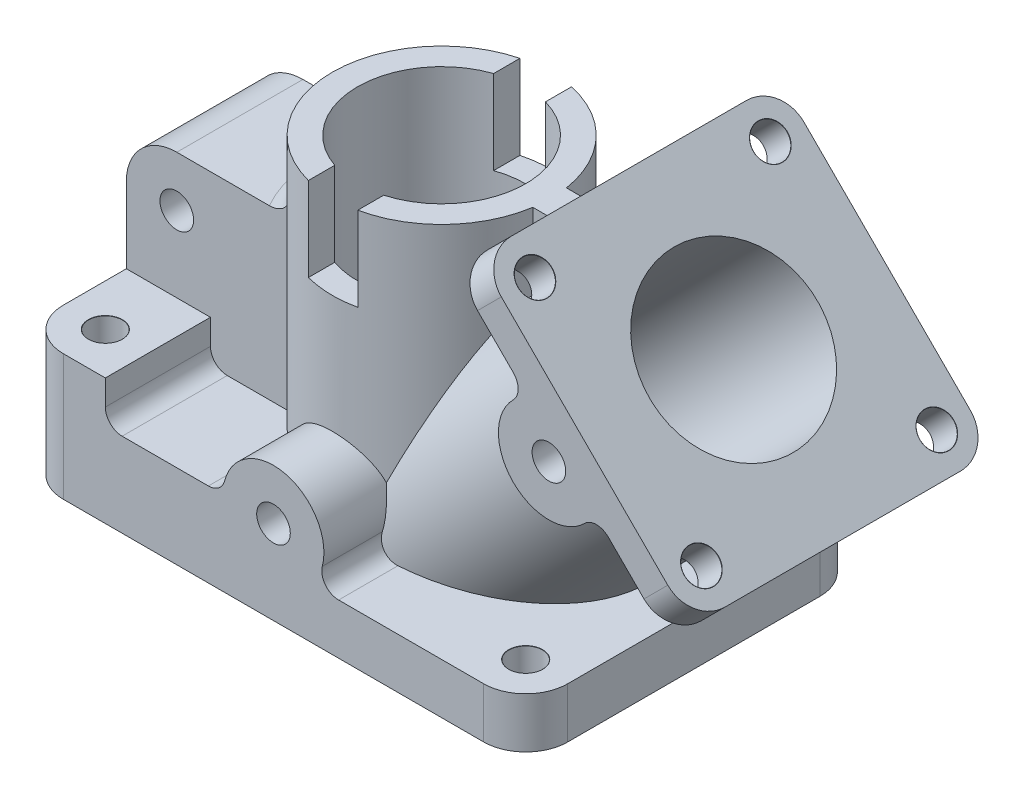
SolidWorks part; units mm, degrees
ref_plane "Front Plane" through (0, 0, 0) normal (0, 0, 1) x (1, 0, 0)
ref_plane "Top Plane" through (0, 0, 0) normal (0, 1, 0) x (1, 0, 0)
ref_plane "Right Plane" through (0, 0, 0) normal (1, 0, 0) x (0, 0, -1)
sketch "Croquis1" plane through (0, 0, 0) normal (0, 0, 1) x (1, 0, 0)
  line L0 (0, 0) -> (0, 15)
  line L1 (0, 15) -> (10, 15)
  line L2 (10, 15) -> (10, 10)
  line L3 (10, 10) -> (24, 10)
  line L4 (34.4721, 6) -> (60, 6)
  line L5 (60, 6) -> (60, 0)
  line L6 (60, 0) -> (0, 0)
  arc A0 (24, 10) -> (34.4721, 6) centre (30, 10) cw
  point P8 (17, 10)
  dimension "D5" = 6
  dimension "D1" = 15
  dimension "D2" = 10
  dimension "D3" = 10
  dimension "D4" = 6
  dimension "D6" = 60
  dimension "D7" = 30
extrude "Saliente-Extruir1" add sketch "Croquis1" along normal mid plane 40
sketch "Croquis2" plane through (0, 0, 20) normal (0, 0, 1) x (1, 0, 0)
  circle A0 centre (30, 10) radius 2
  dimension "D1" = 4
extrude "Cortar-Extruir1" cut sketch "Croquis2" against normal through all
fillet "Redondeo1" radius 2 3 edges at (24, 10, 0) (10, 10, 0) (34.4721, 6, 0)
sketch "Croquis3" plane through (0, 0, 0) normal (0, -1, 0) x (1, 0, 0)
  circle A0 centre (30, 0) radius 13
  dimension "D1" = 26
  dimension "D2" = 30
extrude "Saliente-Extruir2" add sketch "Croquis3" against normal blind 40
sketch "Croquis4" plane through (0, 0, 0) normal (0, 0, 1) x (1, 0, 0)
  line L0 (0, 7.5) -> (0, 30)
  line L1 (0, 15) -> (0, 0) construction
  line L2 (0, 30) -> (19.7656, 30)
  line L3 (19.7656, 30) -> (19.7656, 7.5)
  line L4 (19.7656, 7.5) -> (0, 7.5)
  dimension "D1" = 30
extrude "Saliente-Extruir3" add sketch "Croquis4" along normal mid plane 15
fillet "Redondeo2" radius 2 1 edges at (17, 30, 0)
fillet "Redondeo3" radius 6 1 edges at (0, 30, 0)
sketch "Croquis7" plane through (0, 0, 0) normal (0, 0, 1) x (1, 0, 0)
  line L0 (30, 38.1979) -> (30, 0) construction
  line L1 (0, 0) -> (60, 0) construction
  line L2 (30, 0) -> (65, 35) construction
  point P4 (65, 35)
  point P6 (65, 35)
  point P7 (30, 0)
  dimension "D1" = 45
  dimension "D2" = 35
ref_plane "Plano1" through (65, 35, 0) normal (0.7071, 0.7071, 0) x (0.7071, -0.7071, 0)
sketch "Croquis8" plane through (65, 35, 0) normal (0.7071, 0.7071, 0) x (0.7071, -0.7071, 0)
  line L0 (-27.01, 0) -> (0, 0) construction
  line L1 (18, 18) -> (-18, 18)
  line L2 (18, 18) -> (18, -18)
  line L3 (18, -18) -> (-18, -18)
  line L4 (-18, 18) -> (-18, -18)
  line L5 (18, 18) -> (-18, -18) construction
  line L6 (18, -18) -> (-18, 18) construction
  point P0 (0, 0)
  dimension "D1" = 36
extrude "Saliente-Extruir4" add sketch "Croquis8" against normal blind 4 separate body
sketch "Croquis9" plane through (50, 50, 0) normal (0.7071, 0.7071, 0) x (0, 0, -1)
  line L0 (0, 5.7968) -> (0, -21.2132) construction
  circle A0 centre (0, -21.2132) radius 13
  dimension "D1" = 26
extrude "Saliente-Extruir5" add sketch "Croquis9" against normal blind 41
sketch "Croquis10" plane through (0, 0, 18) normal (0, 0, 1) x (1, 0, 0)
  line L0 (30, 0) -> (65, 35) construction
  line L1 (84.25, 15.75) -> (45.75, 54.25) construction
  circle A0 centre (60.7574, 30.7574) radius 6
  circle A1 centre (60.7574, 30.7574) radius 2
  dimension "D1" = 6
  dimension "D2" = 12
  dimension "D3" = 4
extrude "Saliente-Extruir6" add sketch "Croquis10" against normal blind 36
fillet "Redondeo4" radius 2 4 edges at (66.1716, 28.1716, -14.8523) (58.1716, 36.1716, -14.8523) (66.1716, 28.1716, 14.8523) (58.1716, 36.1716, 14.8523)
fillet "Redondeo5" radius 5 4 edges at (0, 7.5, -20) (60, 3, -20) (0, 7.5, 20) (60, 3, 20)
fillet "Redondeo6" radius 4 4 edges at (76.3137, 20.8579, -18) (50.8579, 46.3137, 18) (50.8579, 46.3137, -18) (76.3137, 20.8579, 18)
hole_wizard "Ø4.0mm Dowel Hole1" positions "Croquis3D1" profile "Croquis12" hole size "Ø4.0" standard "ISO"
sketch3d "Croquis3D1"
  line L0 (52.2721, 42.0711, 14) -> (55.1005, 44.8995, 14) construction
  line L1 (52.2721, 42.0711, -14) -> (55.1005, 44.8995, -14) construction
  line L2 (72.0711, 22.2721, -14) -> (74.8995, 25.1005, -14) construction
  line L3 (72.0711, 22.2721, 14) -> (74.8995, 25.1005, 14) construction
  line L4 (55, 0, 15) -> (55, 6, 15) construction
  line L5 (55, 6, -15) -> (55, 0, -15) construction
  line L6 (5, 0, -15) -> (5, 15, -15) construction
  line L7 (5, 15, 15) -> (5, 0, 15) construction
  point P0 (55.1005, 44.8995, 14)
  point P4 (55.1005, 44.8995, -14)
  point P8 (74.8995, 25.1005, -14)
  point P12 (74.8995, 25.1005, 14)
  point P16 (55, 6, 15)
  point P20 (55, 6, -15)
  point P24 (5, 15, -15)
  point P28 (5, 15, 15)
sketch "Croquis12" plane through (55.1005, 44.8995, 14) normal (0, 0, 1) x (-0.7071, 0.7071, 0)
  line L0 (0, 0) -> (0, 16.2017)
  line L1 (0, 16.2017) -> (2, 15)
  line L2 (2, 15) -> (2, 0.021)
  line L3 (2, 0.021) -> (2.025, 0)
  line L5 (2.025, 0) -> (0, 0)
  line L6 (-2, 0.021) -> (-2.025, 0) construction
  line L10 (0, 16.2017) -> (-2, 15) construction
  line L11 (0, -6.35) -> (0, 107.95) construction
  dimension "Hole Dia." = 4
  dimension "Hole Depth" = 15
  dimension "Near C'Sink Dia." = 4.05
  dimension "Near C'Sink Angle" = 100
  dimension "Drill Angle" = 118
sketch "Croquis15" plane through (0, 0, 0) normal (0, 0, 1) x (1, 0, 0)
  line L0 (34.2168, 40) -> (53.3496, 40)
  line L1 (43, 40) -> (17, 40) construction
  line L2 (53.3496, 40) -> (53.3496, 28.1267)
  line L3 (53.3496, 28.1267) -> (34.2168, 28.1267)
  line L4 (34.2168, 28.1267) -> (34.2168, 40)
extrude "Saliente-Extruir13" add sketch "Croquis15" along normal mid plane 4
sketch "Croquis18" plane through (0, 0, 0) normal (0, 0, 1) x (1, 0, 0)
  line L0 (54.3848, 6) -> (59.9708, 6)
  line L1 (59.9708, 6) -> (71.364, 22.9792)
  line L2 (71.364, 22.9792) -> (54.3848, 6)
  point P3 (59.9241, 6)
  point P6 (0, 0)
  point P7 (59.949, 6)
  point P8 (60.013, 6)
  point P9 (59.9708, 6)
sketch "Croquis20" plane through (0, 40, 0) normal (0, 1, 0) x (1, 0, 0)
  line L0 (30, 0) -> (65, 0) construction
  circle A0 centre (30, 0) radius 10
  dimension "D1" = 20
extrude "Cortar-Extruir3" cut sketch "Croquis20" against normal through all
sketch "Croquis21" plane through (50, 50, 0) normal (0.7071, 0.7071, 0) x (0, 0, -1)
  circle A0 centre (0, -20.8347) radius 10
  dimension "D1" = 20
extrude "Cortar-Extruir4" cut sketch "Croquis21" against normal through all
sketch "Croquis22" plane through (0, 0, 0) normal (0, 0, 1) x (1, 0, 0)
  line L1 (40, 40) -> (20, 40) construction
  line L2 (30, 38.1979) -> (30, 0) construction
  line L5 (26.7337, 30) -> (26.7337, 40)
  line L6 (32.7337, 30) -> (26.7337, 30)
  line L8 (32.7337, 30) -> (32.7337, 40)
  line L9 (32.7337, 40) -> (26.7337, 40)
  point P6 (30, 30)
  point P11 (30, 30)
  dimension "D1" = 6
  dimension "D2" = 10
extrude "Cortar-Extruir5" cut sketch "Croquis22" against normal mid plane 30
sketch "Croquis23" plane through (0, 0, 7.5) normal (0, 0, 1) x (1, 0, 0)
  circle A0 centre (6, 24) radius 2
  dimension "D1" = 4
extrude "Cortar-Extruir6" cut sketch "Croquis23" against normal through all
